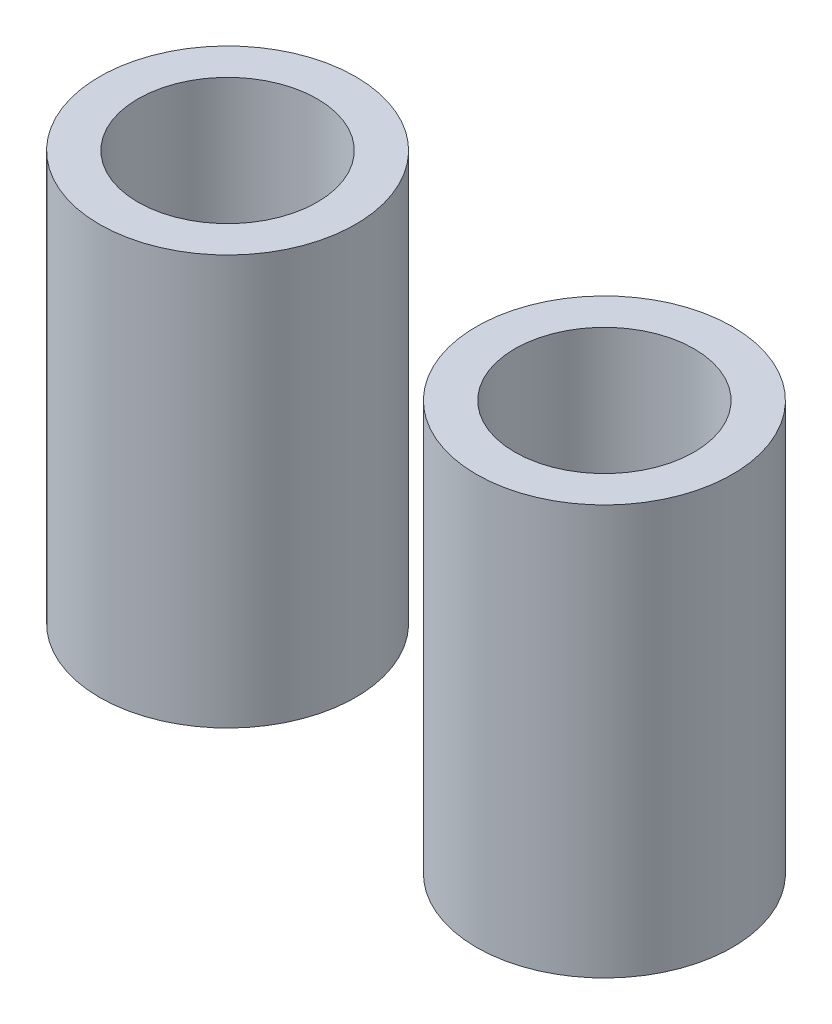
SolidWorks part; units mm, degrees
ref_plane "Alzado" through (0, 0, 0) normal (0, 0, 1) x (1, 0, 0)
ref_plane "Planta" through (0, 0, 0) normal (0, 1, 0) x (1, 0, 0)
ref_plane "Vista lateral" through (0, 0, 0) normal (1, 0, 0) x (0, 0, -1)
sketch "Sketch1" plane through (0, 0, 0) normal (0, 1, 0) x (1, 0, 0)
  circle A0 centre (0, 0) radius 2.5
  circle A1 centre (0, 0) radius 1.75
  dimension "D1" = 5
  dimension "D2" = 3.5
extrude "Boss-Extrude1" add sketch "Sketch1" along normal blind 8
sketch "Sketch2" plane through (0, 0, 0) normal (0, 1, 0) x (1, 0, 0)
  circle A0 centre (7.9068, -0.5477) radius 2.5
  circle A1 centre (7.9068, -0.5477) radius 1.75
  dimension "D1" = 5
  dimension "D2" = 3.5
extrude "Boss-Extrude2" add sketch "Sketch2" along normal blind 8 separate body
